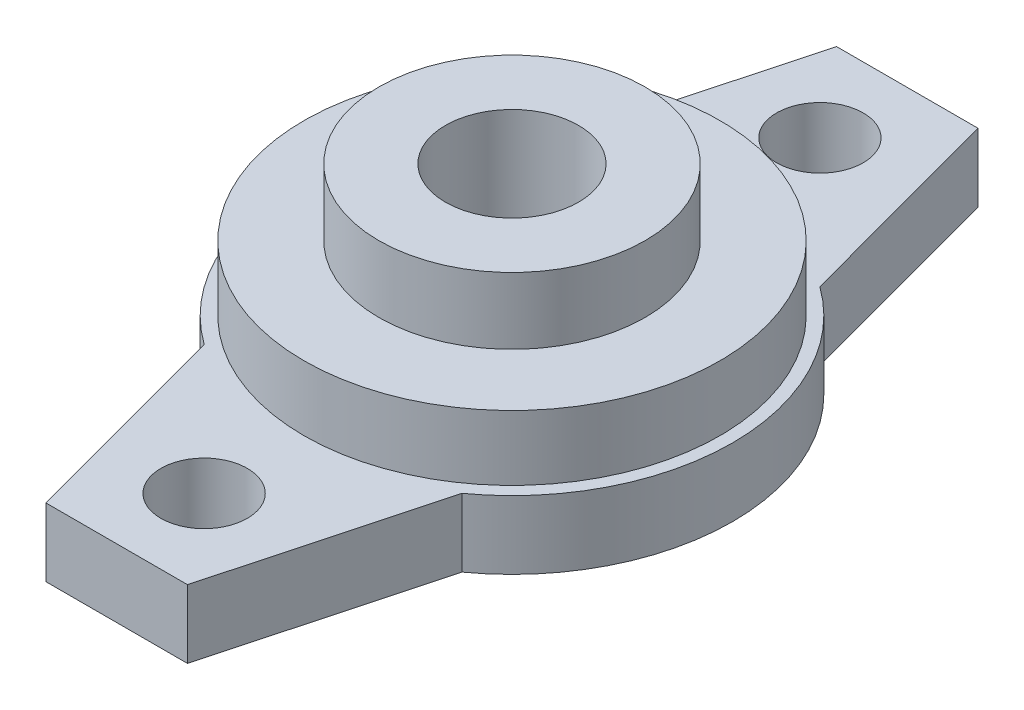
SolidWorks part; units mm, degrees
ref_plane "Front Plane" through (0, 0, 0) normal (0, 0, 1) x (1, 0, 0)
ref_plane "Top Plane" through (0, 0, 0) normal (0, 1, 0) x (1, 0, 0)
ref_plane "Right Plane" through (0, 0, 0) normal (1, 0, 0) x (0, 0, -1)
sketch "Sketch1" plane through (0, 0, 0) normal (0, 1, 0) x (1, 0, 0)
  line L0 (0, 18.5) -> (0, -18.5) construction
  line L1 (13.25, 23.75) -> (-13.25, 23.75)
  line L2 (13.25, 23.75) -> (13.25, -23.75)
  line L3 (13.25, -23.75) -> (-13.25, -23.75)
  line L4 (-13.25, 23.75) -> (-13.25, -23.75)
  line L5 (13.25, 23.75) -> (-13.25, -23.75) construction
  line L6 (13.25, -23.75) -> (-13.25, 23.75) construction
  line L7 (-4.25, 23.75) -> (-7.746, 10.75)
  line L8 (4.25, 23.75) -> (7.746, 10.75)
  line L9 (-13.25, 0) -> (13.25, 0) construction
  line L10 (4.25, -23.75) -> (7.746, -10.75)
  line L11 (-4.25, -23.75) -> (-7.746, -10.75)
  circle A0 centre (0, 0) radius 13.25
  circle A1 centre (0, 18.5) radius 2.6
  circle A2 centre (0, -18.5) radius 2.6
  point P0 (0, 0)
  dimension "D1" = 47.5
  dimension "D4" = 5.2
  dimension "D2" = 26.5
  dimension "D3" = 37
  dimension "D5" = 9
  dimension "D6" = 13
extrude "Boss-Extrude1" add sketch "Sketch1" along normal blind 4.1 contours A0 | A0 L8 L1 L7 A1 | A0 L11 L3 L10 A2
sketch "Sketch2" plane through (0, 4.1, 0) normal (0, 1, 0) x (1, 0, 0)
  circle A0 centre (0, 0) radius 12.5
  dimension "D1" = 25
extrude "Boss-Extrude2" add sketch "Sketch2" along normal blind 3.9 and the other way blind 4.1
sketch "Sketch3" plane through (0, 8, 0) normal (0, 1, 0) x (1, 0, 0)
  circle A0 centre (0, 0) radius 8
  dimension "D1" = 16
extrude "Boss-Extrude3" add sketch "Sketch3" along normal blind 4 and the other way blind 3.9
sketch "Sketch4" plane through (0, 12, 0) normal (0, 1, 0) x (1, 0, 0)
  circle A0 centre (0, 0) radius 4
  dimension "D1" = 8
extrude "Cut-Extrude1" cut sketch "Sketch4" against normal through all
